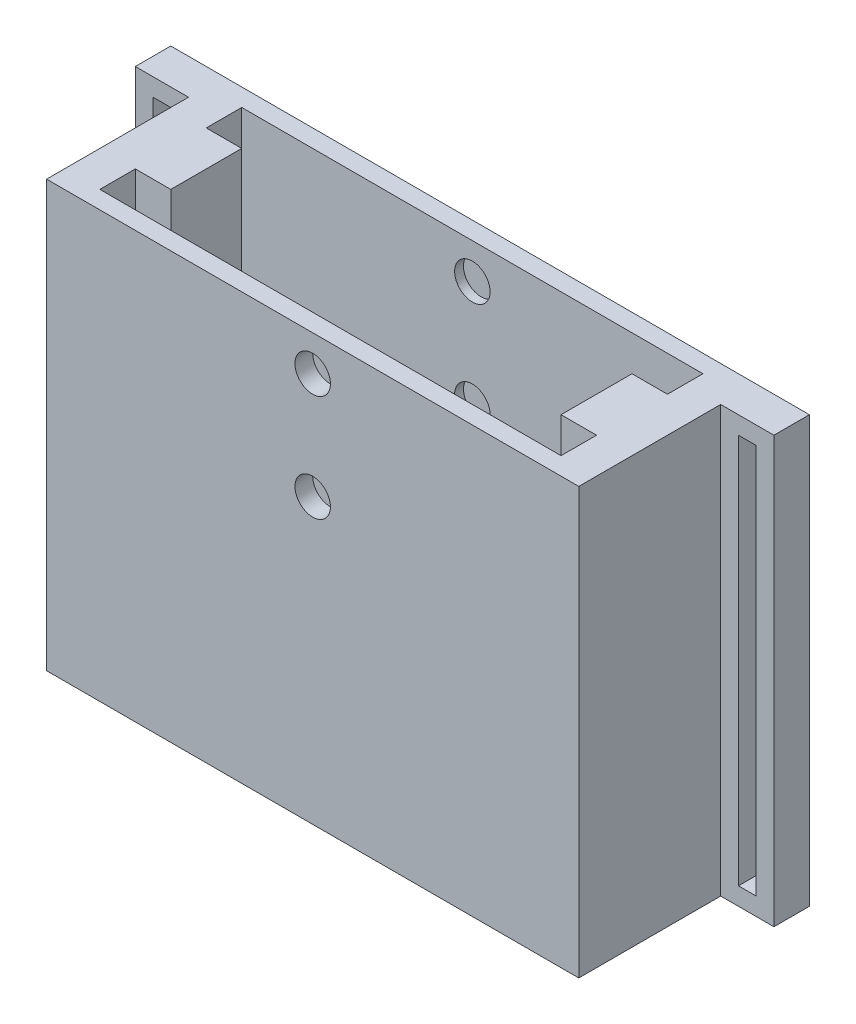
SolidWorks part; units mm, degrees
ref_plane "Front Plane" through (0, 0, 0) normal (0, 0, 1) x (1, 0, 0)
ref_plane "Top Plane" through (0, 0, 0) normal (0, 1, 0) x (1, 0, 0)
ref_plane "Right Plane" through (0, 0, 0) normal (1, 0, 0) x (0, 0, -1)
sketch "Sketch1" plane through (0, 0, 0) normal (0, 0, 1) x (1, 0, 0)
  line L1 (-75, 120) -> (75, 120)
  line L2 (-75, 120) -> (-75, 0)
  line L3 (-75, 0) -> (75, 0)
  line L4 (75, 120) -> (75, 0)
  point P4 (0, 0)
  dimension "D1" = 120
  dimension "D2" = 150
extrude "body" add sketch "Sketch1" along normal blind 50
sketch "Sketch2" plane through (0, 120, 0) normal (0, 1, 0) x (1, 0, 0)
  line L0 (-75, -25) -> (75, -25) construction
  line L1 (-75, -50) -> (-75, 0) construction
  line L2 (75, -50) -> (75, 0) construction
  line L3 (0, -50) -> (0, 0) construction
  line L4 (75, -50) -> (-75, -50) construction
  line L5 (-65, -5) -> (-65, -15)
  line L6 (-65, -15) -> (-55, -15)
  line L7 (-55, -15) -> (-55, -35)
  line L8 (-55, -35) -> (-65, -35)
  line L9 (-65, -35) -> (-65, -45)
  line L10 (-65, -45) -> (65, -45)
  line L11 (-65, -5) -> (65, -5)
  line L12 (65, -35) -> (65, -45)
  line L13 (55, -35) -> (65, -35)
  line L14 (55, -15) -> (55, -35)
  line L15 (65, -15) -> (55, -15)
  line L16 (65, -5) -> (65, -15)
  point P19 (-56.1715, -31.6413)
  point P21 (0, -45)
  point P26 (0, -5)
  dimension "D1" = 10
  dimension "D2" = 10
  dimension "D3" = 130
  dimension "D4" = 40
extrude "spine socket " cut sketch "Sketch2" against normal through all
sketch "Sketch3" plane through (0, 0, 50) normal (0, 0, 1) x (1, 0, 0)
  circle A0 centre (0, 110) radius 5
  circle A1 centre (0, 80) radius 5
  dimension "D1" = 10
  dimension "D2" = 80
  dimension "D3" = 30
extrude "Cut-Extrude2" cut sketch "Sketch3" against normal offset from surface (47.5 mm away) 2.5 up to face at (0, 60, 5) offset beyond the face yes
sketch "Sketch4" plane through (0, 0, 0) normal (0, 0, -1) x (-1, 0, 0)
  line L1 (-90, 120) -> (90, 120)
  line L2 (-90, 120) -> (-90, 0)
  line L3 (-90, 0) -> (90, 0)
  line L4 (90, 120) -> (90, 0)
  line L5 (75, 120) -> (75, 0) construction
  line L6 (-75, 0) -> (-75, 120) construction
  line L7 (75, 120) -> (75, 0)
  line L8 (-75, 0) -> (-75, 120)
  line L9 (-75, 120) -> (75, 120) construction
  line L10 (-85, 115) -> (-80, 115)
  line L11 (-85, 115) -> (-85, 5)
  line L12 (-85, 5) -> (-80, 5)
  line L13 (-80, 115) -> (-80, 5)
  line L14 (0, 120) -> (0, 0) construction
  line L15 (85, 5) -> (80, 5)
  line L16 (85, 115) -> (80, 115)
  line L17 (85, 115) -> (85, 5)
  line L18 (80, 115) -> (80, 5)
  point P4 (0, 0)
  point P21 (-85, 60)
  point P22 (-90, 60)
  line M5 (75, 0) -> (75, 120)
  line M7 (-75, 120) -> (-75, 0)
  dimension "D1" = 5
  dimension "D2" = 180
  dimension "D3" = 5
  dimension "D4" = 5
extrude "Boss-Extrude2" add sketch "Sketch4" against normal blind 10 contours L4 L1 L3 M5 | L2 L3 L1 M7
